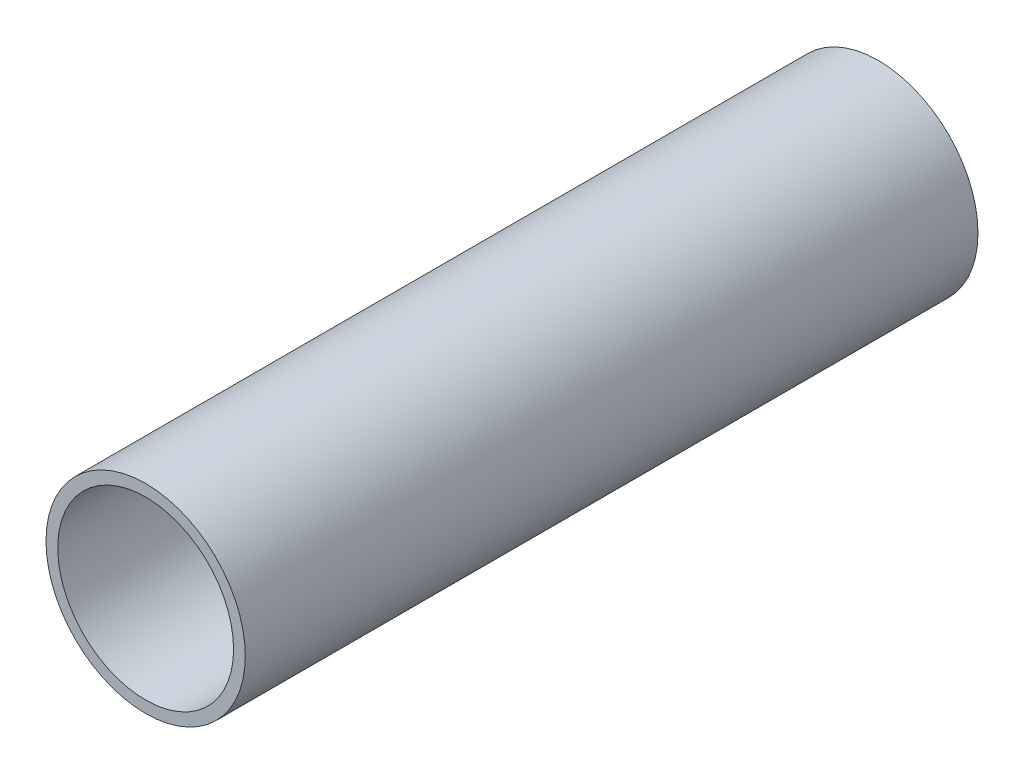
SolidWorks part; units mm, degrees
ref_plane "Front Plane" through (0, 0, 0) normal (1, 0, 0) x (0, 1, 0)
ref_plane "Top Plane" through (0, 0, 0) normal (0, 0, 1) x (0, 1, 0)
ref_plane "Right Plane" through (0, 0, 0) normal (0, 1, 0) x (-1, 0, 0)
sketch "Sketch1" plane through (0, 0, 0) normal (0, 0, 1) x (0, 1, 0)
  circle A0 centre (0, 0) radius 13.6
  circle A1 centre (0, 0) radius 12
  dimension "D1" = 27.2
  dimension "D2" = 24
extrude "Boss-Extrude1" add sketch "Sketch1" along normal blind 100
equation "\"OD\"= 27.2mm"
equation "\"ID\"= 24mm"
equation "\"D1@Sketch1\"=\"OD\""
equation "\"D2@Sketch1\"=\"ID\""
equation "\"L\"= 100mm"
equation "\"D1@Boss-Extrude1\"=\"L\""
